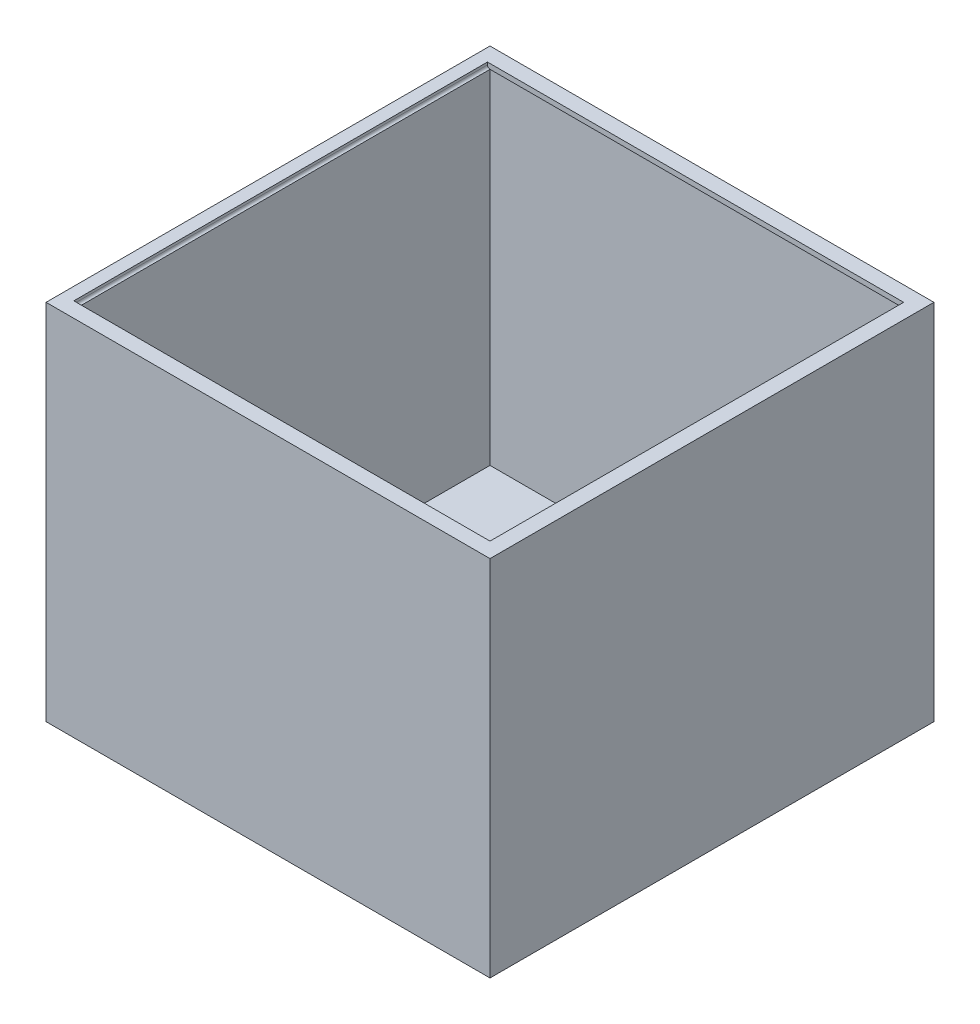
SolidWorks part; units mm, degrees
ref_plane "Спереди" through (0, 0, 0) normal (0, 0, 1) x (1, 0, 0)
ref_plane "Сверху" through (0, 0, 0) normal (0, 1, 0) x (1, 0, 0)
ref_plane "Справа" through (0, 0, 0) normal (1, 0, 0) x (0, 0, -1)
other "Configuration Table"
sketch "Эскиз1" plane through (0, -60, 0) normal (0, 1, 0) x (1, 0, 0)
  line L0 (215, 215) -> (-215, 215)
  line L1 (-215, 215) -> (-215, -215)
  line L2 (-215, -215) -> (215, -215)
  line L3 (215, -215) -> (215, 215)
  line L4 (-220, -220) -> (220, -220)
  line L5 (220, -220) -> (220, 220)
  line L6 (220, 220) -> (-220, 220)
  line L7 (-220, 220) -> (-220, -220)
  line L8 (-220, -220) -> (220, -220)
  line L9 (220, -220) -> (220, 220)
  line L10 (220, 220) -> (-220, 220)
  line L11 (-220, 220) -> (-220, -220)
  dimension "D1" = 0
  dimension "D2" = 5
extrude "Бобышка-Вытянуть1" add sketch "Эскиз1" along normal up to surface (360 mm away)
sketch "Эскиз2" plane through (0, -60, 0) normal (0, 1, 0) x (1, 0, 0)
  line L4 (-220, -220) -> (220, -220)
  line L5 (220, -220) -> (220, 220)
  line L6 (220, 220) -> (-220, 220)
  line L7 (-220, 220) -> (-220, -220)
  line L8 (-220, -220) -> (220, -220)
  line L9 (220, -220) -> (220, 220)
  line L10 (220, 220) -> (-220, 220)
  line L11 (-220, 220) -> (-220, -220)
  dimension "D1" = 0
extrude "Бобышка-Вытянуть2" add sketch "Эскиз2" along normal blind 5
sketch "Эскиз3" plane through (0, 300, 0) normal (0, 1, 0) x (1, 0, 0)
  line L0 (-220, 220) -> (220, 220) construction
  line L1 (-220, 220) -> (220, 220)
  line L2 (220, -220) -> (-220, -220) construction
  line L3 (220, 220) -> (220, -220) construction
  line L4 (-220, -220) -> (-220, 220) construction
  line L5 (220, -220) -> (-220, -220)
  line L6 (220, 220) -> (220, -220)
  line L7 (-220, -220) -> (-220, 220)
  line L12 (-205, 205) -> (205, 205)
  line L13 (205, 205) -> (205, -205)
  line L14 (205, -205) -> (-205, -205)
  line L15 (-205, -205) -> (-205, 205)
  dimension "D1" = 15
extrude "Бобышка-Вытянуть3" add sketch "Эскиз3" against normal blind 5
sketch "Эскиз4" plane through (0, 0, 0) normal (0, 0, 1) x (1, 0, 0)
  line L1 (-205, 295) -> (-205, 300) construction
  line L2 (-205, 295) -> (-205, 300)
  line L3 (-207.5, 297.5) -> (-207.5, 300)
  line L4 (-207.5, 300) -> (-205, 300)
  arc A0 (-207.5, 297.5) -> (-205, 295) centre (-205, 297.5) ccw
  arc A1 (-205, 295) -> (-205, 300) centre (-205, 297.5) ccw construction
  arc A2 (-205, 300) -> (-207.5, 297.5) centre (-205, 297.5) ccw construction
extrude "Вырез-Вытянуть1" cut sketch "Эскиз4" against normal up to surface and the other way up to surface up to face at (0, 297.5, -205) other way up to face at (0, 297.5, 205)
